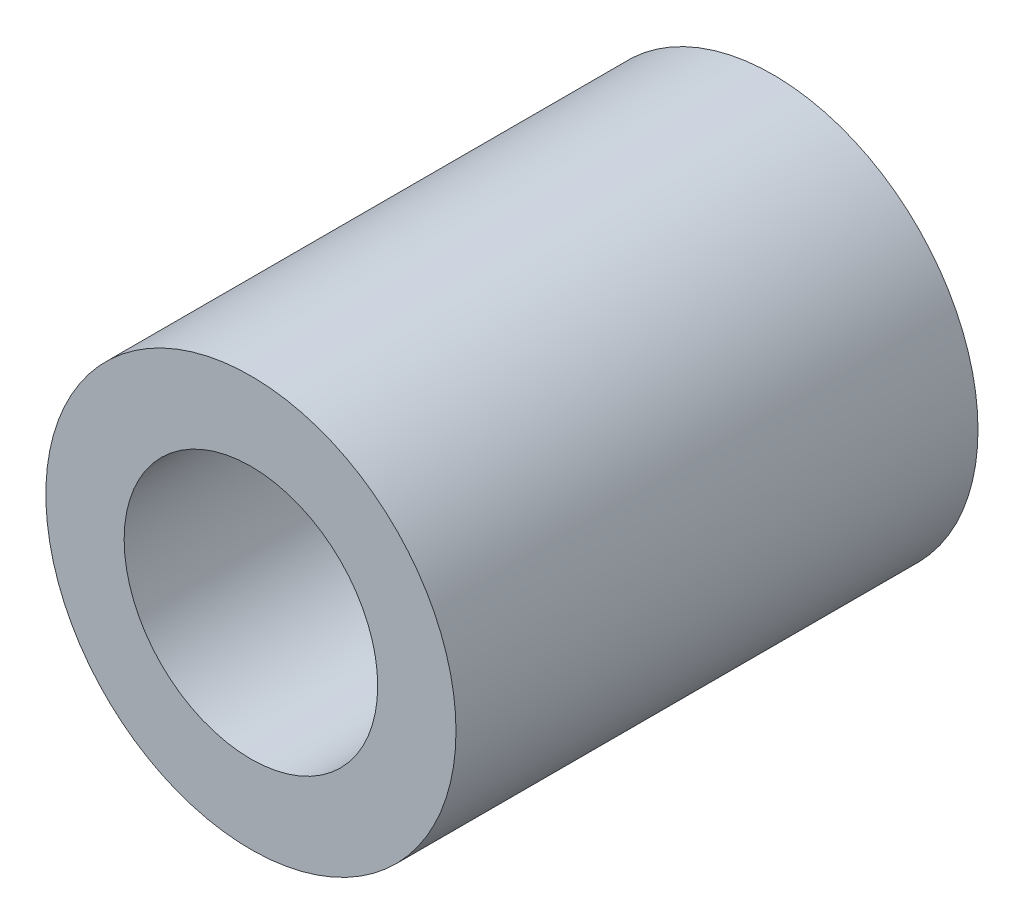
SolidWorks part; units mm, degrees
material "ABS"
ref_plane "前视基准面" through (0, 0, 0) normal (0, 0, 1) x (1, 0, 0)
ref_plane "上视基准面" through (0, 0, 0) normal (0, 1, 0) x (1, 0, 0)
ref_plane "右视基准面" through (0, 0, 0) normal (1, 0, 0) x (0, 0, -1)
sketch "草图1" plane through (0, 0, 0) normal (0, 0, 1) x (1, 0, 0)
  circle A0 centre (0, 0) radius 1.7
  circle A1 centre (0, 0) radius 2.75
  dimension "D1" = 5.5
  dimension "D2" = 3.4
extrude "凸台-拉伸1" add sketch "草图1" along normal blind 7
